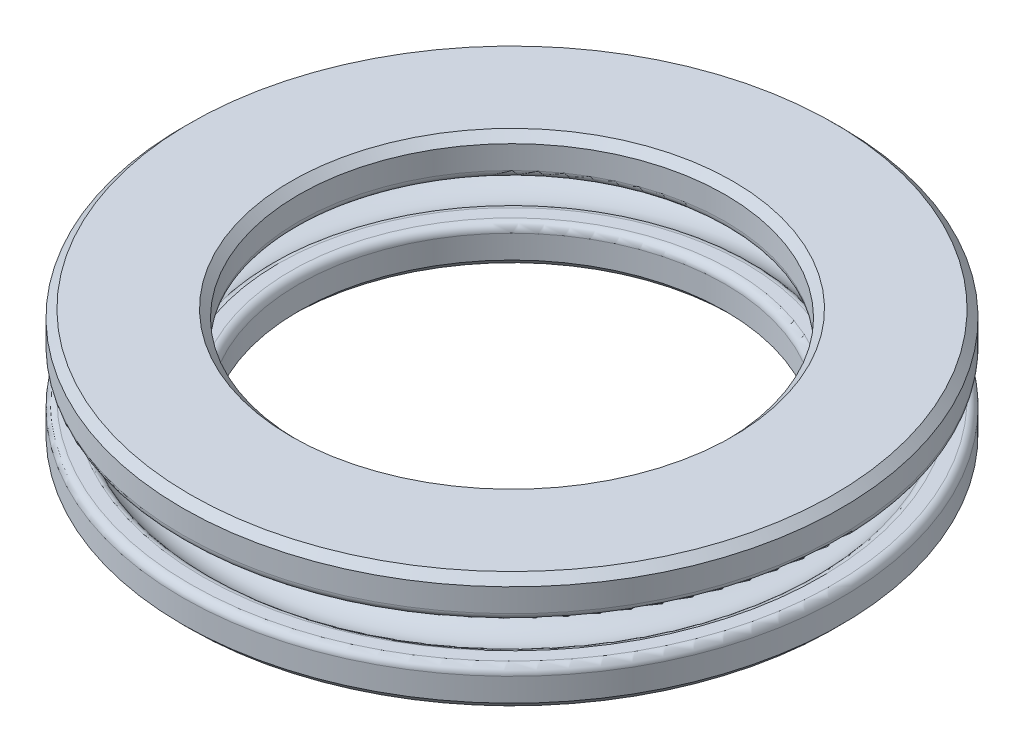
SolidWorks part; units mm, degrees
material "Plain Carbon Steel"
ref_plane "Front Plane" through (0, 0, 0) normal (0, 0, 1) x (1, 0, 0)
ref_plane "Top Plane" through (0, 0, 0) normal (0, 1, 0) x (1, 0, 0)
ref_plane "Right Plane" through (0, 0, 0) normal (1, 0, 0) x (0, 0, -1)
sketch "Sketch1" plane through (0, 0, 0) normal (0, 0, 1) x (1, 0, 0)
  line L0 (0, 36.5523) -> (0, -21.8675) construction
  line L1 (-41.5, 5) -> (-39.8734, 5)
  line L2 (-42.5, 4) -> (-42.5, 1)
  line L3 (-41.5, 0) -> (-28.5, 0)
  line L4 (-27.5, 4) -> (-27.5, 1)
  line L5 (-30.1266, 5) -> (-28.5, 5)
  line L6 (-41.5, 15) -> (-28.5, 15)
  line L7 (-42.5, 14) -> (-42.5, 11)
  line L8 (-41.5, 10) -> (-39.8734, 10)
  line L9 (-27.5, 14) -> (-27.5, 11)
  line L10 (-30.1266, 10) -> (-28.5, 10)
  line L11 (-42.5, 14) -> (-41.5, 15)
  line L12 (-28.5, 0) -> (-27.5, 1)
  line L13 (-42.5, 1) -> (-41.5, 0)
  line L14 (-28.5, 15) -> (-27.5, 14)
  arc A0 (-39.0612, 4.5833) -> (-30.9388, 4.5833) centre (-35, 7.5) ccw
  arc A1 (-30.9388, 10.4167) -> (-39.0612, 10.4167) centre (-35, 7.5) ccw
  arc A2 (-42.5, 11) -> (-41.5, 10) centre (-41.5, 11) ccw
  arc A3 (-39.8734, 10) -> (-39.0612, 10.4167) centre (-39.8734, 11) ccw
  arc A4 (-28.5, 10) -> (-27.5, 11) centre (-28.5, 11) ccw
  arc A5 (-30.9388, 10.4167) -> (-30.1266, 10) centre (-30.1266, 11) ccw
  arc A6 (-30.9388, 4.5833) -> (-30.1266, 5) centre (-30.1266, 4) cw
  arc A7 (-28.5, 5) -> (-27.5, 4) centre (-28.5, 4) cw
  arc A8 (-41.5, 5) -> (-42.5, 4) centre (-41.5, 4) ccw
  arc A9 (-39.0612, 4.5833) -> (-39.8734, 5) centre (-39.8734, 4) ccw
  point P1 (-27.5, 0)
  point P2 (-42.5, 0)
  point P9 (-42.5, 15)
  point P12 (-27.5, 15)
  point P13 (-35, 15)
  point P25 (-30.6699, 10)
  point P28 (-30.6699, 5)
  point P31 (-27.5, 5)
  point P34 (-42.5, 5)
  dimension "D6" = 10
  dimension "D7" = 1
  dimension "D1" = 27.5
  dimension "D2" = 5
  dimension "D3" = 15
  dimension "D4" = 15
  dimension "D5" = 7.5
revolve "Revolve1" add sketch "Sketch1" angle 360 about L0
